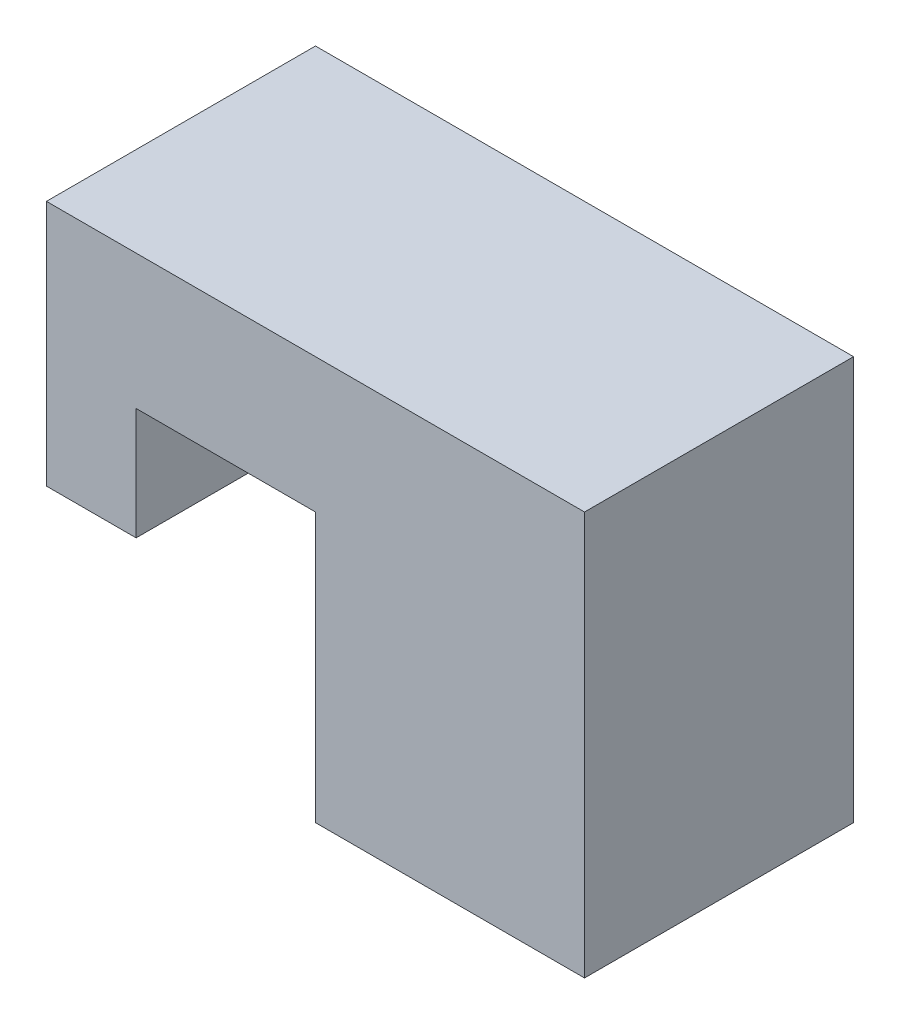
SolidWorks part; units mm, degrees
ref_plane "Front Plane" through (0, 0, 0) normal (0, 0, 1) x (1, 0, 0)
ref_plane "Top Plane" through (0, 0, 0) normal (0, 1, 0) x (1, 0, 0)
ref_plane "Right Plane" through (0, 0, 0) normal (1, 0, 0) x (0, 0, -1)
sketch "Sketch1" plane through (0, 0, 0) normal (0, 1, 0) x (1, 0, 0)
  line L1 (-3, -3) -> (3, -3)
  line L2 (-3, -3) -> (-3, 3)
  line L3 (-3, 3) -> (3, 3)
  line L4 (3, -3) -> (3, 3)
  line L5 (-3, -3) -> (3, 3) construction
  line L6 (-3, 3) -> (3, -3) construction
  point P0 (0, 0)
  dimension "D1" = 6
  dimension "D2" = 6
extrude "Boss-Extrude1" add sketch "Sketch1" along normal blind 6
sketch "Sketch2" plane through (0, 6, 0) normal (0, 1, 0) x (1, 0, 0)
  line L0 (3, 3) -> (3, -3)
  line L1 (3, 3) -> (-9, 3)
  line L2 (3, -3) -> (-9, -3)
  line L3 (-9, 3) -> (-9, -3)
  line L4 (-3, 3) -> (-3, -3) construction
  dimension "D1" = 6
extrude "Boss-Extrude2" add sketch "Sketch2" along normal blind 3
sketch "Sketch3" plane through (0, 6, 0) normal (0, -1, 0) x (1, 0, 0)
  line L0 (-9, 3) -> (-9, -3)
  line L1 (-9, 3) -> (-7, 3)
  line L2 (-9, -3) -> (-7, -3)
  line L3 (-7, 3) -> (-7, -3)
  dimension "D1" = 2
extrude "Boss-Extrude3" add sketch "Sketch3" along normal blind 2.5
